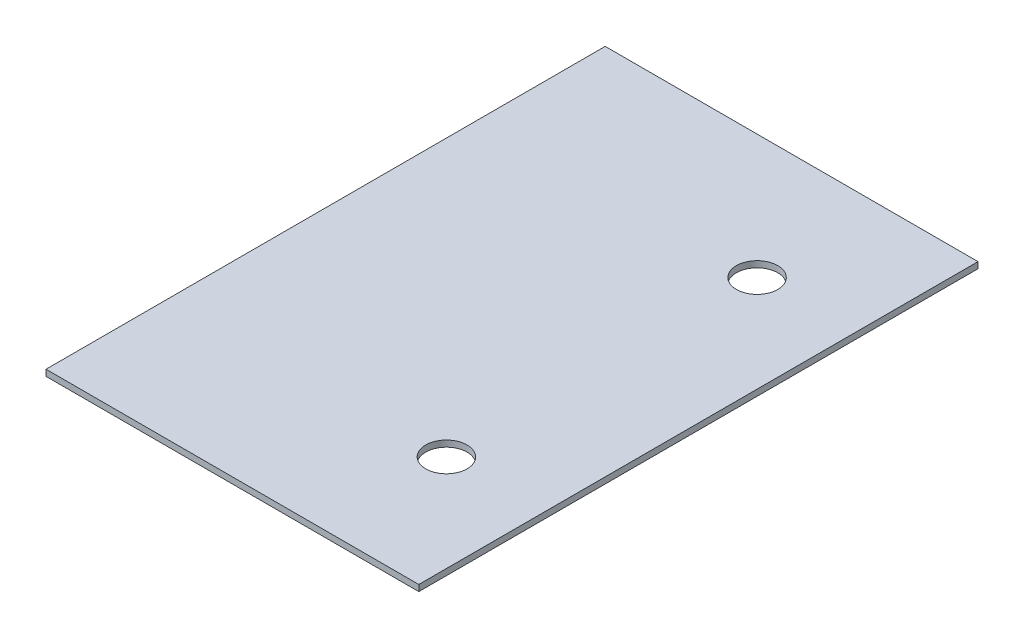
SolidWorks part; units mm, degrees
ref_plane "Front" through (0, 0, 0) normal (0, 0, 1) x (1, 0, 0)
ref_plane "Top" through (0, 0, 0) normal (0, 1, 0) x (1, 0, 0)
ref_plane "Right" through (0, 0, 0) normal (1, 0, 0) x (0, 0, -1)
sketch "Sketch1" plane through (0, 0, 0) normal (0, 1, 0) x (1, 0, 0)
  line L1 (-15, 22.5) -> (15, 22.5)
  line L2 (-15, 22.5) -> (-15, -22.5)
  line L3 (-15, -22.5) -> (15, -22.5)
  line L4 (15, 22.5) -> (15, -22.5)
  line L5 (-15, 22.5) -> (15, -22.5) construction
  line L6 (-15, -22.5) -> (15, 22.5) construction
  point P0 (0, 0)
  dimension "D1" = 30
  dimension "D2" = 45
extrude "Boss-Extrude1" add sketch "Sketch1" along normal blind 0.5
sketch "Sketch2" plane through (0, 0.5, 0) normal (0, 1, 0) x (1, 0, 0)
  line L0 (15, -22.5) -> (15, 22.5) construction
  line L1 (7.2214, -12.5) -> (7.2214, -22.5) construction
  line L2 (-15, -22.5) -> (15, -22.5) construction
  line L3 (7.2214, 12.5) -> (7.2214, 22.5) construction
  line L4 (15, 22.5) -> (-15, 22.5) construction
  line L5 (7.2214, -12.5) -> (7.2214, 12.5) construction
  circle A0 centre (7.2214, 12.5) radius 1.665
  circle A1 centre (7.2214, -12.5) radius 1.665
  dimension "D1" = 3.33
  dimension "D2" = 7.7786
  dimension "D3" = 10
extrude "Cut-Extrude1" cut sketch "Sketch2" against normal up to next
